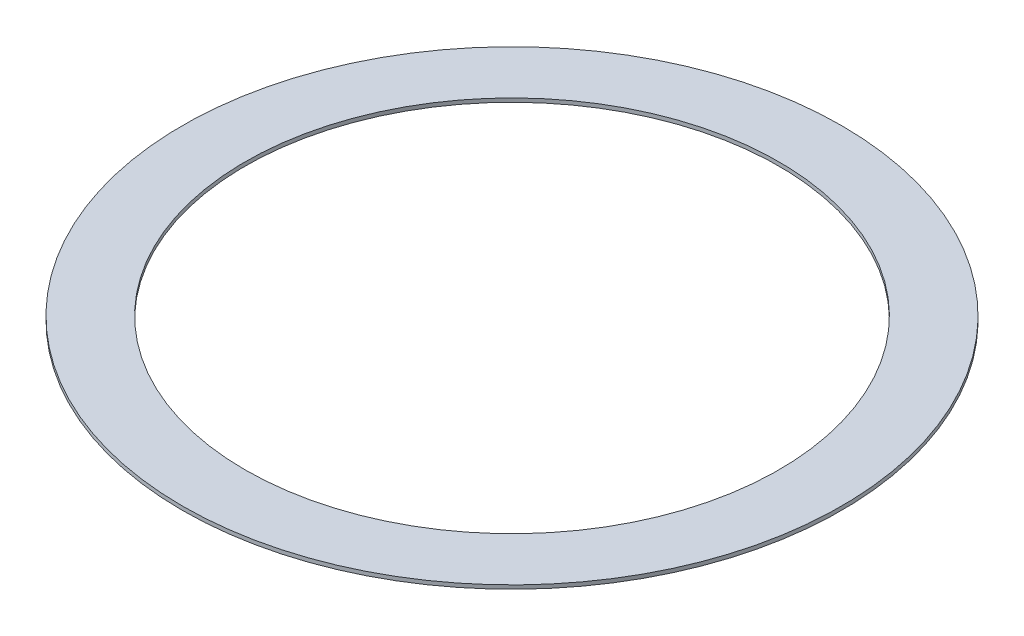
SolidWorks part; units mm, degrees
ref_plane "Front Plane" through (0, 0, 0) normal (0, 0, 1) x (1, 0, 0)
ref_plane "Top Plane" through (0, 0, 0) normal (0, 1, 0) x (1, 0, 0)
ref_plane "Right Plane" through (0, 0, 0) normal (1, 0, 0) x (0, 0, -1)
sketch "Sketch1" plane through (0, 0, 0) normal (0, 1, 0) x (1, 0, 0)
  circle A0 centre (0, 0) radius 352.26
  circle A1 centre (0, 0) radius 435
  dimension "D1" = 704.52
  dimension "D2" = 870
extrude "Boss-Extrude1" add sketch "Sketch1" along normal blind 5
